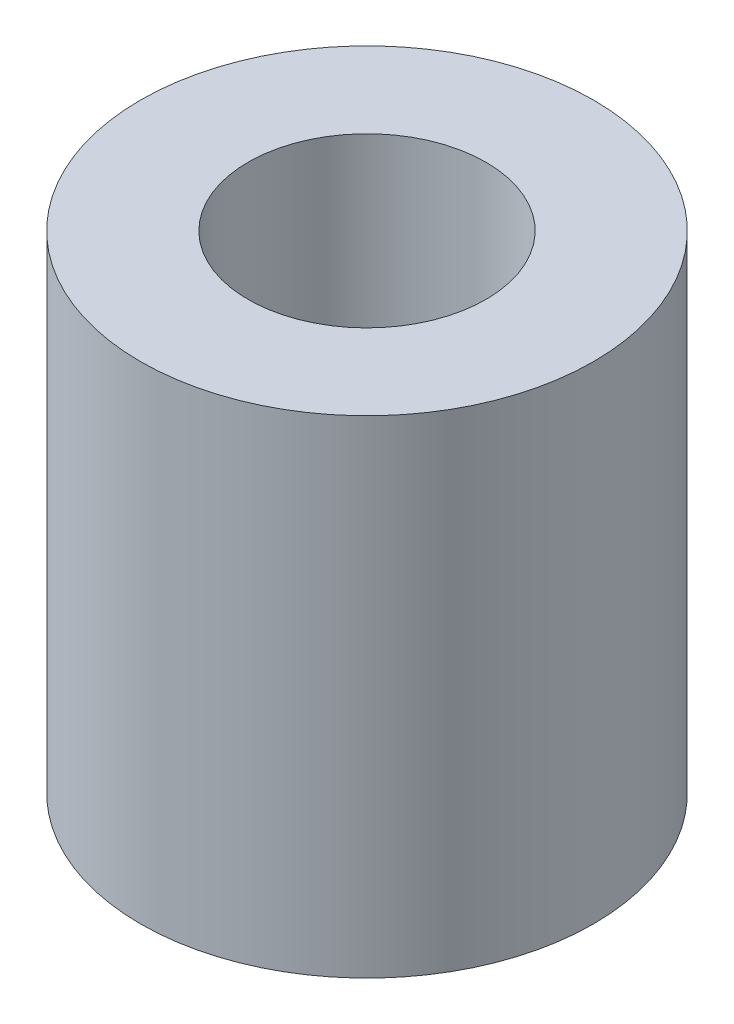
SolidWorks part; units mm, degrees
ref_plane "Front Plane" through (0, 0, 0) normal (0, 0, 1) x (1, 0, 0)
ref_plane "Top Plane" through (0, 0, 0) normal (0, 1, 0) x (1, 0, 0)
ref_plane "Right Plane" through (0, 0, 0) normal (1, 0, 0) x (0, 0, -1)
sketch "Sketch1" plane through (0, 0, 0) normal (0, 1, 0) x (1, 0, 0)
  circle A0 centre (0, 0) radius 2.1
  circle A1 centre (0, 0) radius 4
  dimension "D1" = 4.2
  dimension "D2" = 8
extrude "Boss-Extrude1" add sketch "Sketch1" along normal blind 8.6
